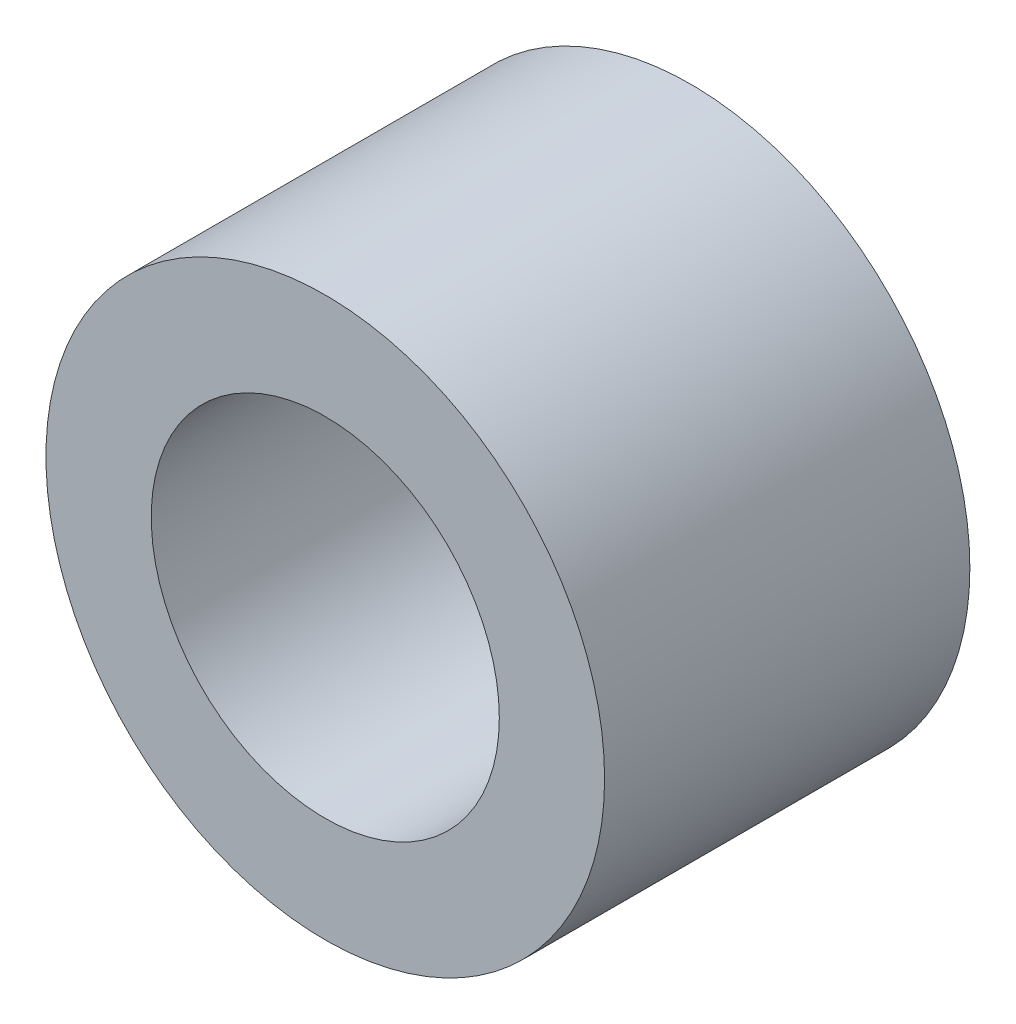
SolidWorks part; units mm, degrees
material "PETG"
ref_plane "Front Plane" through (0, 0, 0) normal (0, 0, 1) x (1, 0, 0)
ref_plane "Top Plane" through (0, 0, 0) normal (0, 1, 0) x (1, 0, 0)
ref_plane "Right Plane" through (0, 0, 0) normal (1, 0, 0) x (0, 0, -1)
sketch "Sketch1" plane through (0, 0, 0) normal (0, 0, 1) x (1, 0, 0)
  circle A0 centre (0, 0) radius 4.05
  circle A1 centre (0, 0) radius 6.5
  dimension "D1" = 8.1
  dimension "D2" = 13
extrude "Boss-Extrude1" add sketch "Sketch1" along normal mid plane 8.5
equation "\"tol_dia_id_intfc\" = 0.0500mm ' For hole diameters - Interference fit"
equation "\"tol_dia_id_slip\"  = 0.0750mm ' For hole diameters - Slip fit"
equation "\"tol_dia_id_clear\" = 0.1000mm ' For hole diameters - Clearance fit"
equation "\"tol_dia_od_intfc\" = 0.0500mm ' For shaft diameters - Interference fit"
equation "\"tol_dia_od_slip\"  = 0.0750mm ' For shaft diameters - Slip fit"
equation "\"tol_dia_od_clear\" = 0.1000mm ' For shaft diameters - Clearance fit"
equation "\"tol_general_intfc\"= 0.0250mm ' For general parts (Horiz) - Interference fit"
equation "\"tol_general_slip\" = 0.0375mm ' For general parts (Horiz) - Slip fit"
equation "\"tol_general_clear\"= 0.0500mm ' For general parts (Horiz) - Clearance fit"
equation "\"tol_layer_intfc\"  = 0.0250mm ' For all parts (Vert) - Interference fit"
equation "\"tol_layer_slip\"   = 0.0375mm ' For all parts (Vert) - Slip fit"
equation "\"tol_layer_clear\"  = 0.0500mm ' For all parts (Vert) - Clearance fit"
equation "\"tol_corner_rad\"   = 0.100mm ' For corners that fit into other parts"
equation "\"D1@Sketch1\"=8.00mm+\"tol_dia_id_clear\""
